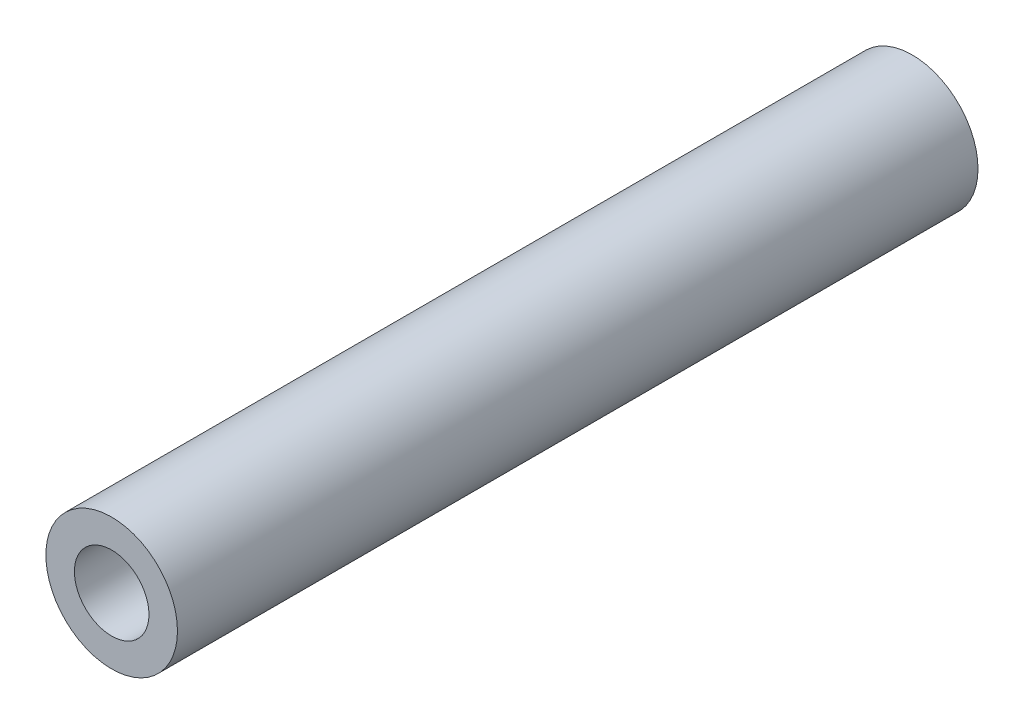
SolidWorks part; units mm, degrees
other "Power Shelf Post 1"
ref_plane "Front Plane" through (0, 0, 0) normal (0, 0, 1) x (1, 0, 0)
ref_plane "Top Plane" through (0, 0, 0) normal (0, 1, 0) x (1, 0, 0)
ref_plane "Right Plane" through (0, 0, 0) normal (1, 0, 0) x (0, 0, -1)
sketch3d "Main Profile Sketch datum points"
  point P0 (0, 0, 85)
  point P1 (10, 0, 85)
  point P2 (0, 10, 85)
ref_plane "Main Profile Sketch plane" through (0, 0, 85) normal (0, 0, 1) x (1, 0, 0)
sketch "Main Profile Sketch" plane through (0, 0, 85) normal (0, 0, 1) x (1, 0, 0)
  circle A0 centre (-234, -51) radius 3
  circle A1 centre (-234, -51) radius 1.7
extrude "Main Extrusion" add sketch "Main Profile Sketch" against normal blind 36.5 separate body
